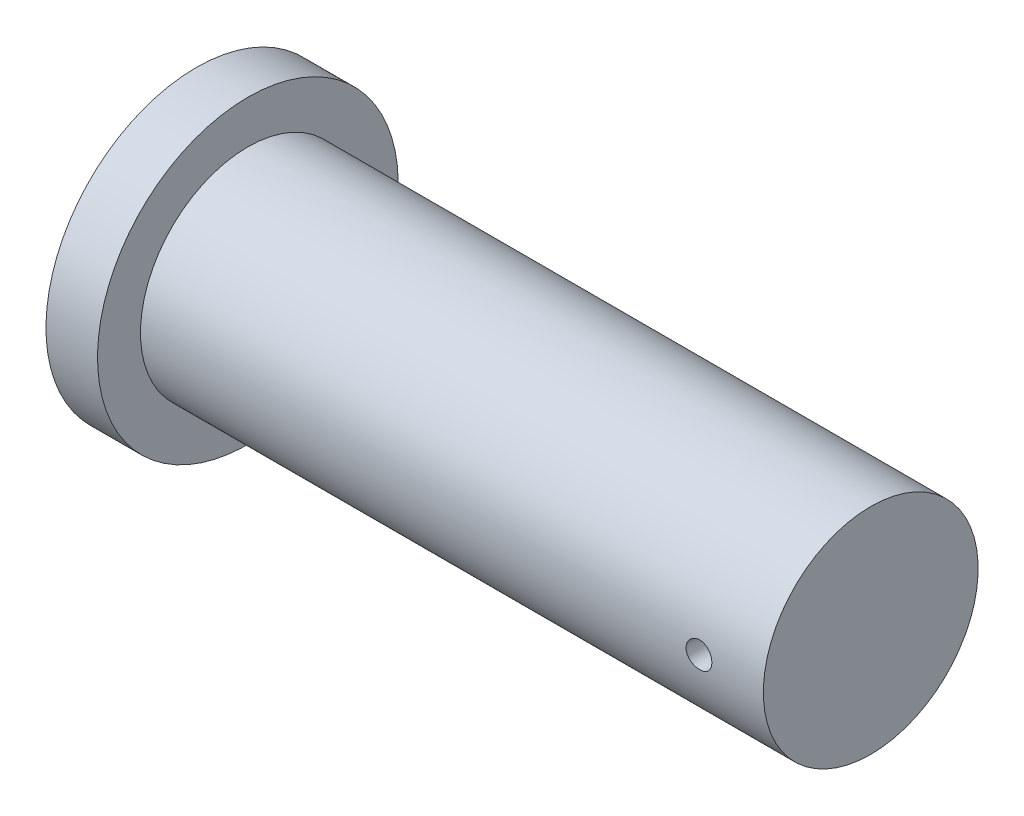
SolidWorks part; units mm, degrees
ref_plane "Front Plane" through (0, 0, 0) normal (0, 0, 1) x (1, 0, 0)
ref_plane "Top Plane" through (0, 0, 0) normal (0, 1, 0) x (1, 0, 0)
ref_plane "Right Plane" through (0, 0, 0) normal (1, 0, 0) x (0, 0, -1)
sketch "Sketch1" plane through (0, 0, 0) normal (0, 0, 1) x (1, 0, 0)
  line L0 (0, 0) -> (-157, 0)
  line L1 (-157, 0) -> (-157, 35)
  line L2 (-157, 35) -> (-145, 35)
  line L3 (-145, 35) -> (-145, 25)
  line L4 (-145, 25) -> (0, 25)
  line L5 (0, 25) -> (0, 0)
  point P7 (0, 0)
  point P8 (0, 0)
  dimension "D1" = 157
  dimension "D2" = 12
  dimension "D3" = 25
  dimension "D4" = 35
revolve "Revolve1" add sketch "Sketch1" angle 360 about L0
sketch "Sketch2" plane through (0, 0, 0) normal (0, 0, 1) x (1, 0, 0)
  line L0 (-145, -35) -> (-145, 35) construction
  circle A0 centre (-15, 0) radius 3
  point P5 (0, 0)
  point P7 (-16.2135, 1.5367)
  point P8 (-222.7424, -16.4936)
  dimension "D1" = 6
  dimension "D2" = 130
extrude "Cut-Extrude1" cut sketch "Sketch2" against normal through all both and the other way through all
